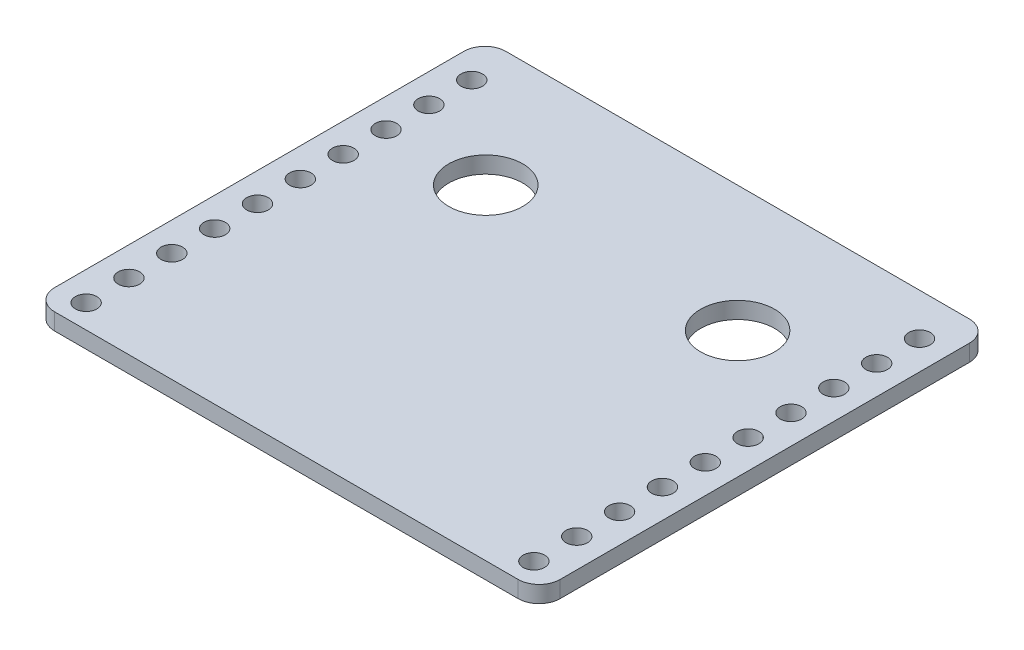
SolidWorks part; units mm, degrees
ref_plane "Front Plane" through (0, 0, 0) normal (0, 0, 1) x (1, 0, 0)
ref_plane "Top Plane" through (0, 0, 0) normal (0, 1, 0) x (1, 0, 0)
ref_plane "Right Plane" through (0, 0, 0) normal (1, 0, 0) x (0, 0, -1)
sketch "Sketch1" plane through (0, 0, 0) normal (0, 1, 0) x (1, 0, 0)
  line L0 (0, 0) -> (0, -50000) construction
  line L1 (-48.175, 43) -> (48.175, 43)
  line L2 (-48.175, 43) -> (-48.175, -43)
  line L3 (-48.175, -43) -> (48.175, -43)
  line L4 (48.175, 43) -> (48.175, -43)
  line L5 (-48.175, 43) -> (48.175, -43) construction
  line L6 (-48.175, -43) -> (48.175, 43) construction
  line L7 (42.675, 1.2802) -> (42.675, -49998.7198) construction
  line L8 (21.7767, 35) -> (-49978.2233, 35) construction
  circle A0 centre (42.675, 35) radius 2.05
  circle A1 centre (42.675, 26.8327) radius 2.05
  circle A2 centre (42.675, 18.6653) radius 2.05
  circle A3 centre (42.675, 10.498) radius 2.05
  circle A4 centre (42.675, 2.3306) radius 2.05
  circle A5 centre (42.675, -5.8367) radius 2.05
  circle A6 centre (42.675, -14.004) radius 2.05
  circle A7 centre (42.675, -22.1714) radius 2.05
  circle A8 centre (42.675, -30.3387) radius 2.05
  circle A9 centre (42.675, -38.506) radius 2.05
  circle A10 centre (-42.675, -38.506) radius 2.05
  circle A11 centre (-42.675, -30.3387) radius 2.05
  circle A12 centre (-42.675, -22.1714) radius 2.05
  circle A13 centre (-42.675, -14.004) radius 2.05
  circle A14 centre (-42.675, -5.8367) radius 2.05
  circle A15 centre (-42.675, 2.3306) radius 2.05
  circle A16 centre (-42.675, 10.498) radius 2.05
  circle A17 centre (-42.675, 18.6653) radius 2.05
  circle A18 centre (-42.675, 26.8327) radius 2.05
  circle A19 centre (-42.675, 35) radius 2.05
  point P0 (0, 0)
  dimension "D5" = 4.1
  dimension "D1" = 86
  dimension "D2" = 96.35
  dimension "D3" = 5.5
  dimension "D4" = 8
  dimension "D6" = 10
extrude "Boss-Extrude1" add sketch "Sketch1" along normal blind 3.175
fillet "Fillet1" radius 4 4 edges at (-48.175, 1.5875, -43) (48.175, 1.5875, -43) (48.175, 1.5875, 43) (-48.175, 1.5875, 43)
sketch "Sketch2" plane through (0, 3.175, 0) normal (0, 1, 0) x (1, 0, 0)
  line L0 (0, 0) -> (0, -50000) construction
  line L1 (0, 0) -> (50000, 0) construction
  line L2 (20.2816, 19) -> (50020.2816, 19) construction
  line L3 (44.175, 43) -> (-44.175, 43) construction
  line L4 (-16.4821, -12.3343) -> (7.5179, 28.6514) construction
  line L5 (40.4821, 9.3486) -> (16.4821, -31.6372) construction
  line L6 (0, -21.9857) -> (50000, -21.9857) construction
  line L7 (-16, -5.9857) -> (16, -5.9857) construction
  line L8 (-16, -5.9857) -> (-16, -37.9857) construction
  line L9 (-16, -37.9857) -> (16, -37.9857) construction
  line L10 (16, -5.9857) -> (16, -37.9857) construction
  line L11 (-16, -5.9857) -> (16, -37.9857) construction
  line L12 (-16, -37.9857) -> (16, -5.9857) construction
  line L13 (-10.05, -31.9857) -> (30.25, -31.9857) construction
  line L14 (-10.05, -31.9857) -> (-10.05, -11.9857) construction
  line L15 (-10.05, -11.9857) -> (30.25, -11.9857) construction
  line L16 (30.25, -31.9857) -> (30.25, -11.9857) construction
  line L17 (-10.05, -31.9857) -> (30.25, -11.9857) construction
  line L18 (-10.05, -11.9857) -> (30.25, -31.9857) construction
  line L19 (0, -11.9857) -> (0, -31.9857) construction
  line L20 (-17.9, -8.0357) -> (-14.9, -8.0357) construction
  line L21 (41.6, -1.9857) -> (-21.4, -1.9857) construction
  line L22 (41.6, -1.9857) -> (41.6, -41.9857) construction
  line L23 (41.6, -41.9857) -> (-21.4, -41.9857) construction
  line L24 (-21.4, -1.9857) -> (-21.4, -41.9857) construction
  line L25 (41.6, -1.9857) -> (-21.4, -41.9857) construction
  line L26 (41.6, -41.9857) -> (-21.4, -1.9857) construction
  line L27 (38.1, -5.9857) -> (-17.9, -5.9857) construction
  line L28 (38.1, -5.9857) -> (38.1, -37.9857) construction
  line L29 (38.1, -37.9857) -> (-17.9, -37.9857) construction
  line L30 (-17.9, -5.9857) -> (-17.9, -37.9857) construction
  line L31 (38.1, -5.9857) -> (-17.9, -37.9857) construction
  line L32 (38.1, -37.9857) -> (-17.9, -5.9857) construction
  line L33 (-14.9, -3.9357) -> (-17.9, -3.9357) construction
  line L34 (-6.9, -3.9357) -> (-9.9, -3.9357) construction
  line L35 (-9.9, -8.0357) -> (-6.9, -8.0357) construction
  line L36 (1.1, -3.9357) -> (-1.9, -3.9357) construction
  line L37 (-1.9, -8.0357) -> (1.1, -8.0357) construction
  line L38 (9.1, -3.9357) -> (6.1, -3.9357) construction
  line L39 (6.1, -8.0357) -> (9.1, -8.0357) construction
  line L40 (17.1, -3.9357) -> (14.1, -3.9357) construction
  line L41 (14.1, -8.0357) -> (17.1, -8.0357) construction
  line L42 (25.1, -3.9357) -> (22.1, -3.9357) construction
  line L43 (22.1, -8.0357) -> (25.1, -8.0357) construction
  line L44 (33.1, -3.9357) -> (30.1, -3.9357) construction
  line L45 (30.1, -8.0357) -> (33.1, -8.0357) construction
  line L46 (-14.9, -8.0357) -> (-6.9, -8.0357) construction
  line L47 (30.1, -35.9357) -> (33.1, -35.9357) construction
  line L48 (33.1, -40.0357) -> (30.1, -40.0357) construction
  line L49 (14.1, -35.9357) -> (17.1, -35.9357) construction
  line L50 (17.1, -40.0357) -> (14.1, -40.0357) construction
  line L51 (-17.9, -35.9357) -> (-14.9, -35.9357) construction
  line L52 (-14.9, -40.0357) -> (-17.9, -40.0357) construction
  circle A1 centre (-24, 19) radius 24.8 construction
  circle A3 centre (0, -21.9857) radius 19.1 construction
  circle A4 centre (24, 19) radius 19.1 construction
  arc A6 (-16.4821, -12.3343) -> (16.4821, -31.6372) centre (0, -21.9857) ccw construction
  arc A7 (7.5179, 28.6514) -> (40.4821, 9.3486) centre (24, 19) cw construction
  circle A8 centre (-24, 19) radius 7.05
  circle A9 centre (24, 19) radius 7.05
  circle A11 centre (-16, -5.9857) radius 2.05 construction
  circle A12 centre (16, -5.9857) radius 2.05 construction
  circle A13 centre (16, -37.9857) radius 2.05 construction
  circle A14 centre (-16, -37.9857) radius 2.05 construction
  circle A15 centre (0, -21.9857) radius 12 construction
  arc A16 (-17.9, -3.9357) -> (-17.9, -8.0357) centre (-17.9, -5.9857) ccw construction
  circle A17 centre (38.1, -5.9857) radius 2.05 construction
  circle A18 centre (-17.9, -37.9857) radius 2.05 construction
  circle A19 centre (38.1, -37.9857) radius 2.05 construction
  arc A21 (-14.9, -8.0357) -> (-14.9, -3.9357) centre (-14.9, -5.9857) ccw construction
  arc A22 (-6.9, -8.0357) -> (-6.9, -3.9357) centre (-6.9, -5.9857) ccw construction
  arc A23 (-9.9, -3.9357) -> (-9.9, -8.0357) centre (-9.9, -5.9857) ccw construction
  arc A24 (1.1, -8.0357) -> (1.1, -3.9357) centre (1.1, -5.9857) ccw construction
  arc A25 (-1.9, -3.9357) -> (-1.9, -8.0357) centre (-1.9, -5.9857) ccw construction
  arc A26 (9.1, -8.0357) -> (9.1, -3.9357) centre (9.1, -5.9857) ccw construction
  arc A27 (6.1, -3.9357) -> (6.1, -8.0357) centre (6.1, -5.9857) ccw construction
  arc A28 (17.1, -8.0357) -> (17.1, -3.9357) centre (17.1, -5.9857) ccw construction
  arc A29 (14.1, -3.9357) -> (14.1, -8.0357) centre (14.1, -5.9857) ccw construction
  arc A30 (25.1, -8.0357) -> (25.1, -3.9357) centre (25.1, -5.9857) ccw construction
  arc A31 (22.1, -3.9357) -> (22.1, -8.0357) centre (22.1, -5.9857) ccw construction
  arc A32 (33.1, -8.0357) -> (33.1, -3.9357) centre (33.1, -5.9857) ccw construction
  arc A33 (30.1, -3.9357) -> (30.1, -8.0357) centre (30.1, -5.9857) ccw construction
  arc A34 (33.1, -35.9357) -> (33.1, -40.0357) centre (33.1, -37.9857) cw construction
  arc A35 (30.1, -40.0357) -> (30.1, -35.9357) centre (30.1, -37.9857) cw construction
  arc A36 (17.1, -35.9357) -> (17.1, -40.0357) centre (17.1, -37.9857) cw construction
  arc A37 (14.1, -40.0357) -> (14.1, -35.9357) centre (14.1, -37.9857) cw construction
  arc A38 (-17.9, -40.0357) -> (-17.9, -35.9357) centre (-17.9, -37.9857) cw construction
  arc A39 (-14.9, -35.9357) -> (-14.9, -40.0357) centre (-14.9, -37.9857) cw construction
  point P31 (10.1, -21.9857)
  point P36 (10.1, -21.9857)
  point P45 (10.1, -21.9857)
  dimension "D1" = 38.2
  dimension "D4" = 49.6
  dimension "D7" = 14.1
  dimension "D10" = 4.1
  dimension "D11" = 24
  dimension "D19" = 4.1
  dimension "D21" = 2.05
  dimension "D2" = 48
  dimension "D3" = 24
  dimension "D5" = 24
  dimension "D8" = 32
  dimension "D9" = 32
  dimension "D12" = 40.3
  dimension "D13" = 20
  dimension "D14" = 10.05
  dimension "D15" = 63
  dimension "D16" = 40
  dimension "D17" = 56
  dimension "D18" = 32
  dimension "D20" = 3
  dimension "D23" = 8
  dimension "D22" = 7
extrude "Cut-Extrude1" cut sketch "Sketch2" against normal blind 3.18
equation "\"w\"= 96.35mm"
equation "\"h\"= 86mm"
equation "\"D1@Sketch1\"=\"h\""
equation "\"D2@Sketch1\"=\"w\""
equation "\"sh\"= 4.1mm"
equation "\"D5@Sketch1\"=\"sh\""
equation "\"thick\"= 3.175mm"
equation "\"D1@Boss-Extrude1\"=\"thick\""
equation "\"ptich diameter\"= 38.2mm"
equation "\"gearC2C\"= 48mm"
equation "\"D1@Sketch2\"=\"ptich diameter\""
equation "\"D2@Sketch2\"=\"gearC2C\""
equation "\"D3@Sketch2\"=\"gearC2C\"/2"
equation "\"60 Tooth Hub-Mount Gear\"= 49.6mm"
equation "\"D4@Sketch2\"=\"60 Tooth Hub-Mount Gear\""
equation "\"pathLength\"= 215mm"
equation "\"D6@Sketch2\"=\"pathLength\""
equation "\"bearingID\"= 14.1mm"
equation "\"D7@Sketch2\"=\"bearingID\""
equation "\"pillowMountHoles\"= 32mm"
equation "\"D8@Sketch2\"=\"pillowMountHoles\""
equation "\"D9@Sketch2\"=\"pillowMountHoles\""
equation "\"D10@Sketch2\"=\"sh\""
equation "\"servow\"= 40.3mm"
equation "\"servoh\"= 20mm"
equation "\"D12@Sketch2\"=\"servow\""
equation "\"D13@Sketch2\"=\"servoh\""
equation "\"servoMountW\"= 63mm"
equation "\"servoMountH\"= 40mm"
equation "\"D15@Sketch2\"=\"servoMountW\""
equation "\"D16@Sketch2\"=\"servoMountH\""
equation "\"servoMountHoleW\"= \"servoMountW\" - 7mm"
equation "\"servoMountHoleH\"= \"servoMountH\" - 8mm"
equation "\"D17@Sketch2\"=\"servoMountHoleW\""
equation "\"D18@Sketch2\"=\"servoMountHoleH\""
equation "\"D19@Sketch2\"=\"sh\""
equation "\"D21@Sketch2\"=\"sh\"/2"
